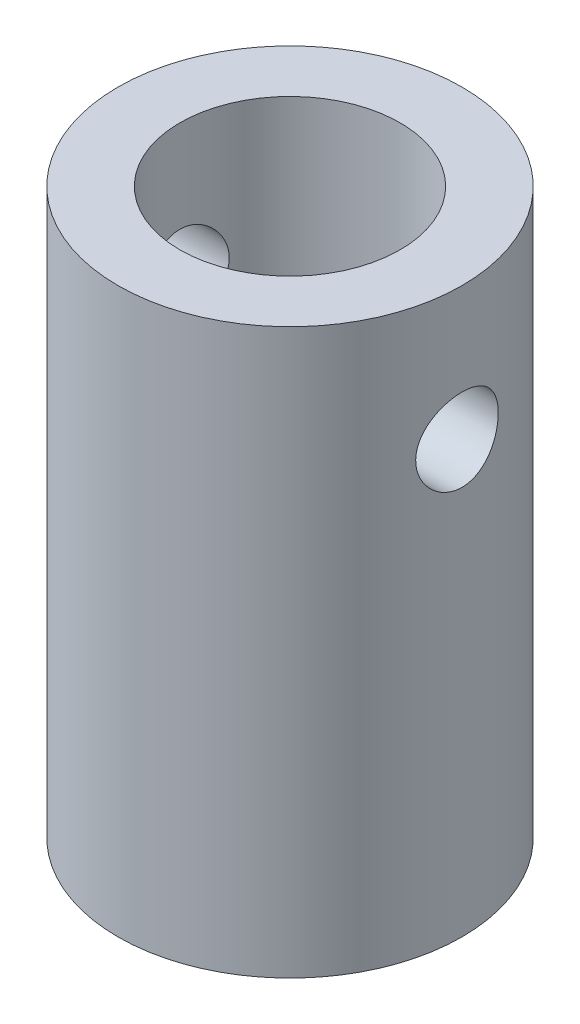
SolidWorks part; units mm, degrees
ref_plane "前视基准面" through (0, 0, 0) normal (0, 0, 1) x (1, 0, 0)
ref_plane "上视基准面" through (0, 0, 0) normal (0, 1, 0) x (1, 0, 0)
ref_plane "右视基准面" through (0, 0, 0) normal (1, 0, 0) x (0, 0, -1)
sketch "草图1" plane through (0, 0, 0) normal (0, 1, 0) x (1, 0, 0)
  circle A0 centre (0, 0) radius 12.5
  circle A1 centre (0, 0) radius 8.001
extrude "凸台-拉伸1" add sketch "草图1" along normal blind 41
ref_plane "基准面1" through (0, 41, 0) normal (0, 1, 0) x (1, 0, 0)
sketch "草图2" plane through (0, 41, 0) normal (0, 1, 0) x (1, 0, 0)
  circle A0 centre (0, 0) radius 8
sketch "草图4" plane through (0, 0, 0) normal (1, 0, 0) x (0, 0, -1)
  line L0 (0, 55) -> (0, -55) construction
  line L1 (12.5, 41) -> (-12.5, 41) construction
  circle A0 centre (0, 31.3) radius 3
  dimension "D1" = 9.7
extrude "切除-拉伸2" cut sketch "草图4" against normal through all both and the other way through all
